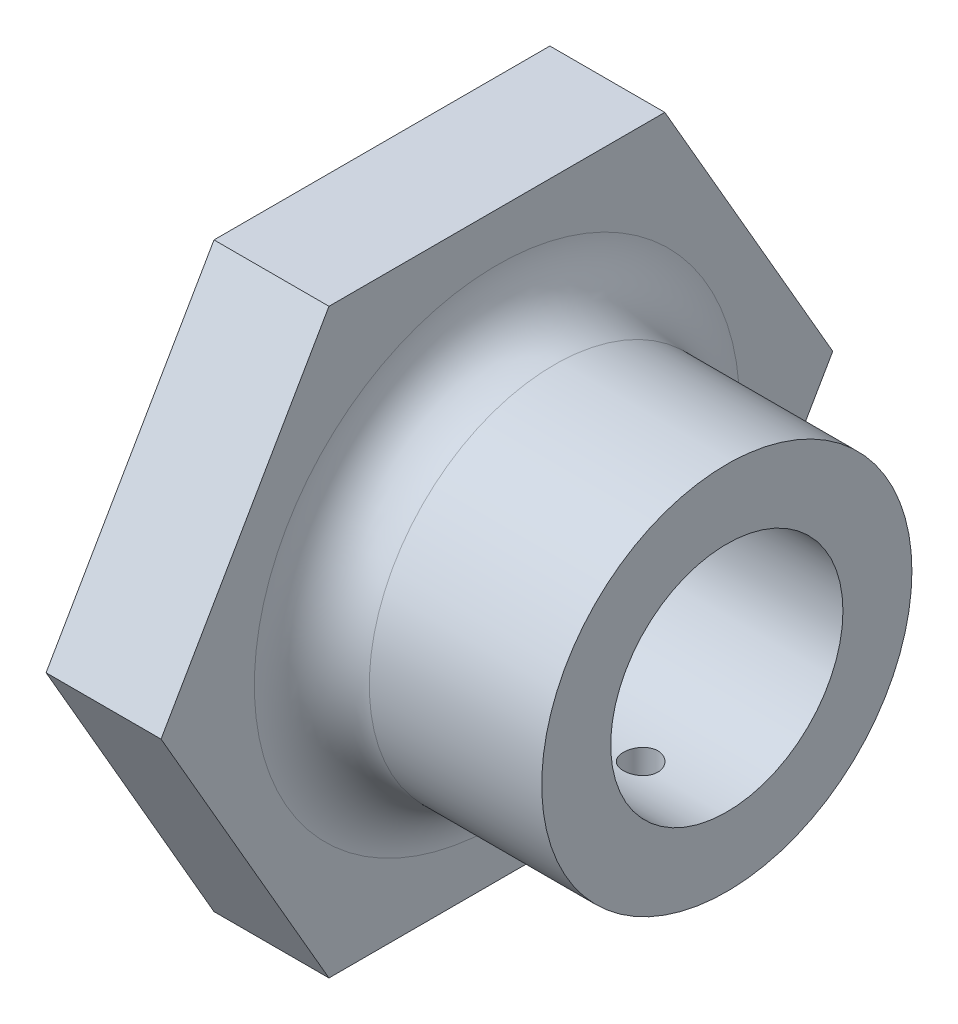
SolidWorks part; units mm, degrees
ref_plane "Front Plane" through (0, 0, 0) normal (0, 0, 1) x (1, 0, 0)
ref_plane "Top Plane" through (0, 0, 0) normal (0, 1, 0) x (1, 0, 0)
ref_plane "Right Plane" through (0, 0, 0) normal (1, 0, 0) x (0, 0, -1)
sketch "Sketch1" plane through (0, 0, 0) normal (1, 0, 0) x (0, 0, -1)
  line L0 (14.607, 25.3) -> (-14.607, 25.3)
  line L1 (-14.607, 25.3) -> (-29.2139, 0)
  line L2 (-29.2139, 0) -> (-14.607, -25.3)
  line L3 (-14.607, -25.3) -> (14.607, -25.3)
  line L4 (14.607, -25.3) -> (29.2139, 0)
  line L5 (29.2139, 0) -> (14.607, 25.3)
  circle A1 centre (0, 0) radius 10.1
extrude "Boss-Extrude1" add sketch "Sketch1" along normal blind 10
sketch "Sketch2" plane through (10, 0, 0) normal (1, 0, 0) x (0, 0, -1)
  circle A0 centre (0, 0) radius 10.1 construction
  circle A1 centre (0, 0) radius 10.1
  circle A2 centre (0, 0) radius 16.1
  dimension "D1" = 6
extrude "Boss-Extrude2" add sketch "Sketch2" along normal blind 20
fillet "Fillet1" radius 5 1 edges at (10, 0, -16.1)
sketch "Sketch3" plane through (0, 0, 0) normal (0, 1, 0) x (1, 0, 0)
  line L0 (30, 0) -> (15, 0)
  line L1 (30, -16.1) -> (30, 16.1) construction
  line L2 (15, 16.1) -> (15, -16.1) construction
  circle A0 centre (22.5, 0) radius 1.5
extrude "Cut-Extrude1" cut sketch "Sketch3" against normal blind 20 contours L0 A0 | L0 A0
